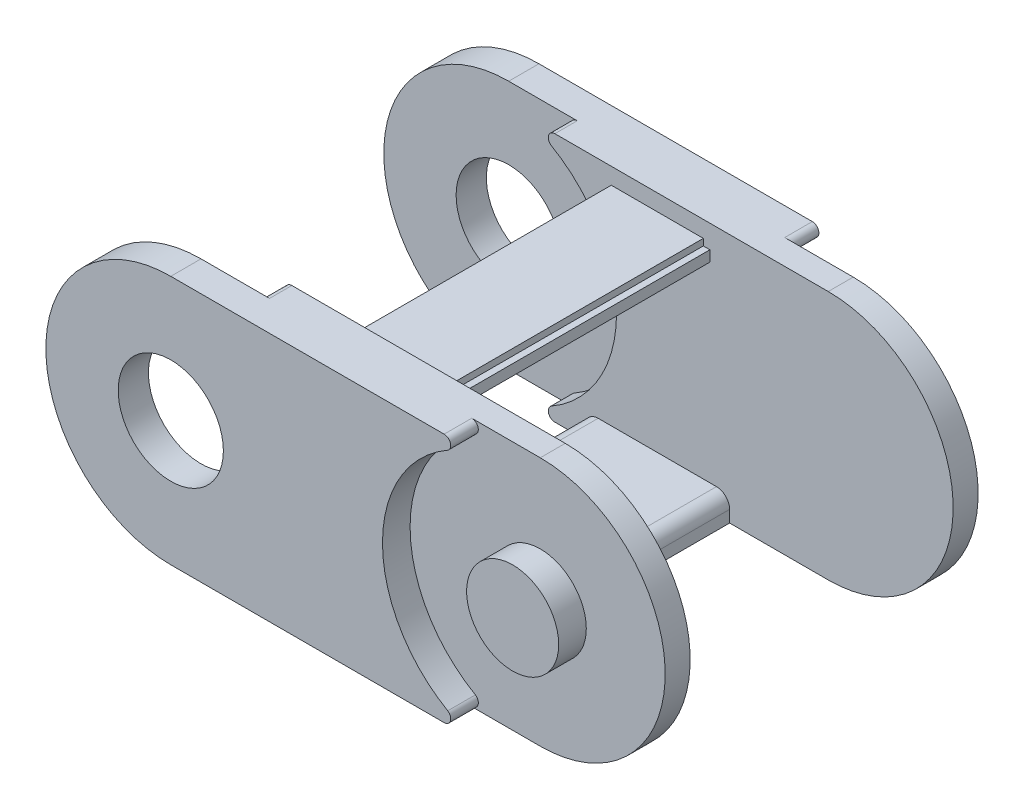
SolidWorks part; units mm, degrees
ref_plane "Front" through (0, 0, 0) normal (0, 0, 1) x (1, 0, 0)
ref_plane "Top" through (0, 0, 0) normal (0, 1, 0) x (1, 0, 0)
ref_plane "Right" through (0, 0, 0) normal (1, 0, 0) x (0, 0, -1)
ref_plane "Plano1" through (0, 0, -10) normal (0, 0, 1) x (1, 0, 0)
sketch "Croquis1" plane through (0, 0, -10) normal (0, 0, 1) x (1, 0, 0)
  line L0 (-13, -9.5) -> (13, -9.5)
  line L1 (13, 9.5) -> (-13, 9.5)
  arc A0 (-13, 9.5) -> (-13, -9.5) centre (-13, 0) ccw
  arc A1 (13, -9.5) -> (13, 9.5) centre (13, 0) ccw
extrude "Saliente-Extruir1" add sketch "Croquis1" against normal blind 4
sketch "Croquis2" plane through (0, 0, -10) normal (0, 0, 1) x (1, 0, 0)
  line L0 (13, -7.6) -> (13, -9.5)
  line L1 (13, -9.5) -> (-13, -9.5)
  line L2 (-13, -9.5) -> (-13, -7.6)
  line L3 (-13, -7.6) -> (13, -7.6)
extrude "Saliente-Extruir2" add sketch "Croquis2" along normal blind 20
sketch "Croquis3" plane through (0, 0, -10) normal (0, 0, 1) x (1, 0, 0)
  line L0 (-6.2732, 7.75) -> (6.2732, 7.75)
  arc A0 (6.2732, 7.75) -> (-6.2732, 7.75) centre (0, 21.65) cw
extrude "Saliente-Extruir3" add sketch "Croquis3" along normal blind 20
sketch "Croquis4" plane through (0, 0, 10) normal (0, 0, 1) x (1, 0, 0)
  line L0 (-13, 9.5) -> (13, 9.5)
  line L1 (13, -9.5) -> (-13, -9.5)
  arc A0 (13, 9.5) -> (13, -9.5) centre (13, 0) cw
  arc A1 (-13, -9.5) -> (-13, 9.5) centre (-13, 0) cw
extrude "Saliente-Extruir4" add sketch "Croquis4" along normal blind 1.9
sketch "Croquis5" plane through (-13, 0, 0) normal (-1, 0, 0) x (0, 0, 1)
  line L0 (-10, -7.6) -> (-10, -9.5)
  line L1 (-10, -9.5) -> (10, -9.5)
  line L2 (10, -9.5) -> (10, -7.6)
  line L3 (10, -7.6) -> (-10, -7.6)
extrude "Cortar-Extruir1" cut sketch "Croquis5" against normal blind 5.21
sketch "Croquis6" plane through (0, 0, 10) normal (0, 0, -1) x (-1, 0, 0)
  line L0 (7.79, -9.5) -> (13, -9.5)
  line L1 (13, 9.5) -> (7.79, 9.5)
  arc A0 (13, -9.5) -> (13, 9.5) centre (13, 0) ccw
  arc A1 (7.79, 9.5) -> (8.0635, 8.5814) centre (7.79, 9) cw
  arc A2 (8.0635, 8.5814) -> (8.0635, -8.5814) centre (13, 0) ccw
  arc A3 (8.0635, -8.5814) -> (7.79, -9.5) centre (7.79, -9) cw
extrude "Cortar-Extruir2" cut sketch "Croquis6" against normal blind 1.7
sketch "Croquis7" plane through (-7.79, 0, 0) normal (-1, 0, 0) x (0, 0, 1)
  line L0 (-10, -7.6) -> (-10, -9.5)
  line L1 (-10, -9.5) -> (10, -9.5)
  line L2 (10, -9.5) -> (10, -7.6)
  line L3 (10, -7.6) -> (-10, -7.6)
extrude "Cortar-Extruir3" cut sketch "Croquis7" against normal blind 2.29
ref_plane "Plano2" through (0, 0, -10) normal (0, 0, -1) x (-1, 0, 0)
sketch "Croquis8" plane through (0, 0, -10) normal (0, 0, -1) x (-1, 0, 0)
  line L0 (4, 7.75) -> (4, 6.9339)
  line L1 (6.2732, 7.75) -> (4, 7.75)
  arc A0 (4, 6.9339) -> (6.2732, 7.75) centre (0, 21.65) ccw
extrude "Cortar-Extruir4" cut sketch "Croquis8" against normal blind 20
sketch "Croquis9" plane through (0, 0, -10) normal (0, 0, -1) x (-1, 0, 0)
  line L0 (-4, 6.9339) -> (-4, 7.75)
  line L1 (-4, 7.75) -> (-6.2732, 7.75)
  arc A0 (-6.2732, 7.75) -> (-4, 6.9339) centre (0, 21.65) ccw
extrude "Cortar-Extruir5" cut sketch "Croquis9" against normal blind 20
sketch "Croquis10" plane through (0, 0, -10) normal (0, 0, 1) x (1, 0, 0)
  line L0 (-7.79, 9.5) -> (-13, 9.5)
  line L1 (-13, -9.5) -> (-7.79, -9.5)
  arc A0 (-7.79, -9.5) -> (-8.0635, -8.5814) centre (-7.79, -9) cw
  arc A1 (-8.0635, -8.5814) -> (-8.0635, 8.5814) centre (-13, 0) ccw
  arc A2 (-8.0635, 8.5814) -> (-7.79, 9.5) centre (-7.79, 9) cw
  arc A3 (-13, 9.5) -> (-13, -9.5) centre (-13, 0) ccw
extrude "Cortar-Extruir6" cut sketch "Croquis10" against normal blind 1.7
sketch "Croquis11" plane through (0, 0, -14) normal (0, 0, -1) x (-1, 0, 0)
  line L0 (-13, -9.5) -> (-7.79, -9.5)
  line L1 (-7.79, 9.5) -> (-13, 9.5)
  arc A0 (-7.79, -9.5) -> (-8.0635, -8.5814) centre (-7.79, -9) cw
  arc A1 (-8.0635, -8.5814) -> (-8.0635, 8.5814) centre (-13, 0) ccw
  arc A2 (-8.0635, 8.5814) -> (-7.79, 9.5) centre (-7.79, 9) cw
  arc A3 (-13, 9.5) -> (-13, -9.5) centre (-13, 0) ccw
extrude "Cortar-Extruir7" cut sketch "Croquis11" against normal blind 2.1
sketch "Croquis12" plane through (13, 0, 0) normal (1, 0, 0) x (0, 0, -1)
  line L0 (10, -9.5) -> (10, -7.6)
  line L1 (10, -7.6) -> (-10, -7.6)
  line L2 (-10, -7.6) -> (-10, -9.5)
  line L3 (-10, -9.5) -> (10, -9.5)
extrude "Cortar-Extruir8" cut sketch "Croquis12" against normal blind 7.5
sketch "Croquis13" plane through (0, 0, 11.9) normal (0, 0, 1) x (1, 0, 0)
  line L0 (7.79, -9.5) -> (-13, -9.5)
  line L1 (-13, 9.5) -> (7.79, 9.5)
  arc A0 (8.0635, 8.5814) -> (8.0635, -8.5814) centre (13, 0) ccw
  arc A1 (8.0635, -8.5814) -> (7.79, -9.5) centre (7.79, -9) cw
  arc A2 (-13, -9.5) -> (-13, 9.5) centre (-13, 0) cw
  arc A3 (7.79, 9.5) -> (8.0635, 8.5814) centre (7.79, 9) cw
extrude "Saliente-Extruir5" add sketch "Croquis13" along normal blind 2.1
sketch "Croquis14" plane through (0, 0, 0) normal (0, 1, 0) x (1, 0, 0)
  line L0 (16.5, -11.9) -> (13, -11.9)
  line L1 (13, -11.9) -> (13, -14)
  line L2 (13, -14) -> (16.5, -14)
  line L3 (16.5, -14) -> (16.5, -11.9)
  line L4 (13, -11.9) -> (13, -14) construction
revolve "Revolución1" add sketch "Croquis14" angle 360 about L4
ref_plane "Plano3" through (0, 0, 0) normal (0, -1, 0) x (1, 0, 0)
sketch "Croquis15" plane through (0, 0, 0) normal (0, -1, 0) x (1, 0, 0)
  line L0 (16.5, -11.9) -> (13, -11.9)
  line L1 (13, -11.9) -> (13, -14)
  line L2 (13, -14) -> (16.5, -14)
  line L3 (16.5, -14) -> (16.5, -11.9)
  line L4 (13, -11.9) -> (13, -14) construction
revolve "Revolución2" add sketch "Croquis15" angle 360 about L4
hole_wizard "Diámetro de taladro Ø7.0 (7)1" positions "Croquis17" profile "Croquis16" hole size "Ø7.0" standard "Ansi Metric"
sketch "Croquis17" plane through (0, 0, 11.7) normal (0, 0, -1) x (-1, 0, 0)
  point P0 (13, 0)
sketch "Croquis16" plane through (-13, 0, 11.7) normal (1, 0, 0) x (0, 1, 0)
  line L0 (0, 0) -> (0, 2.3)
  line L1 (0, 2.3) -> (3.5, 2.3)
  line L2 (3.5, 2.3) -> (3.5, 0)
  line L5 (3.5, 0) -> (0, 0)
  line L11 (0, -6.35) -> (0, 107.95) construction
  dimension "Diámetro de taladro hasta el siguiente" = 7
  dimension "Profundidad de taladro hasta el siguiente" = 2.3
hole_wizard "Diámetro de taladro Ø7.0 (7)2" positions "Croquis19" profile "Croquis18" hole size "Ø7.0" standard "Ansi Metric"
sketch "Croquis19" plane through (0, 0, -14) normal (0, 0, -1) x (-1, 0, 0)
  point P0 (13, 0)
sketch "Croquis18" plane through (-13, 0, -14) normal (1, 0, 0) x (0, 1, 0)
  line L0 (0, 0) -> (0, 28)
  line L1 (0, 28) -> (3.5, 28)
  line L2 (3.5, 28) -> (3.5, 0)
  line L5 (3.5, 0) -> (0, 0)
  line L11 (0, -6.35) -> (0, 107.95) construction
  dimension "Diámetro de taladro hasta el siguiente" = 7
  dimension "Profundidad de taladro hasta el siguiente" = 28
ref_plane "Plano4" through (0, 0, 0) normal (-1, 0, 0) x (0, -1, 0)
sketch "Croquis20" plane through (0, 0, 0) normal (-1, 0, 0) x (0, -1, 0)
  line L0 (-8.25, 10) -> (-8.25, -10)
rib "Nervio1" sketch "Croquis20" sketch "Croquis20" thickness 7 extrusion direction parallel to sketch draft on no parameters "D1"=7
fillet "Redondeo1" radius 1 2 edges at (5.5, -7.6, 0) (-5.5, -7.6, 0)
sketch "Croquis21" plane through (0, 0, 14) normal (0, 0, 1) x (1, 0, 0)
  circle A0 centre (-13, 0) radius 4
  dimension "D1" = 8
extrude "Cortar-Extruir9" cut sketch "Croquis21" against normal blind 34
